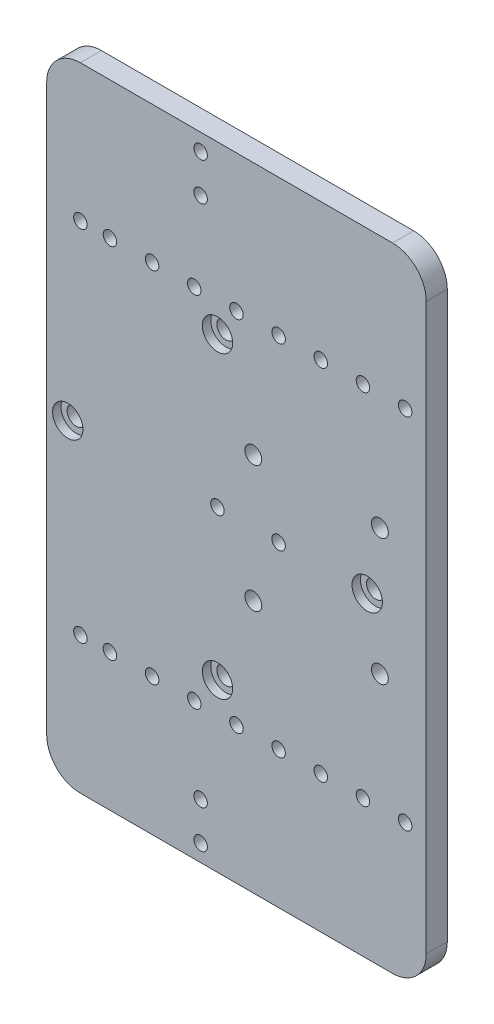
SolidWorks part; units mm, degrees
ref_plane "前视基准面" through (0, 0, 0) normal (0, 0, 1) x (1, 0, 0)
ref_plane "上视基准面" through (0, 0, 0) normal (0, 1, 0) x (1, 0, 0)
ref_plane "右视基准面" through (0, 0, 0) normal (1, 0, 0) x (0, 0, -1)
sketch "草图1" plane through (0, 0, 0) normal (0, 0, 1) x (1, 0, 0)
  line L1 (0, 0) -> (90, 0)
  line L2 (0, 0) -> (0, -150)
  line L3 (0, -150) -> (90, -150)
  line L4 (90, 0) -> (90, -150)
  circle A4 centre (79, -60) radius 2
  circle A5 centre (79, -90) radius 2
  circle A12 centre (49, -60) radius 2
  circle A13 centre (49, -90) radius 2
  circle A14 centre (40.5, -39.5) radius 2.15
  circle A15 centre (40.5, -110.5) radius 2.15
  circle A16 centre (76, -75) radius 2.15
  circle A17 centre (5, -75) radius 2.15
  circle A18 centre (85, -117.5) radius 1.6
  circle A19 centre (75, -117.5) radius 1.6
  circle A20 centre (65, -117.5) radius 1.6
  circle A21 centre (55, -117.5) radius 1.6
  circle A22 centre (45, -117.5) radius 1.6
  circle A23 centre (85, -32.5) radius 1.6
  circle A24 centre (75, -32.5) radius 1.6
  circle A25 centre (65, -32.5) radius 1.6
  circle A26 centre (55, -32.5) radius 1.6
  circle A27 centre (45, -32.5) radius 1.6
  circle A28 centre (35, -117.5) radius 1.6
  circle A29 centre (25, -117.5) radius 1.6
  circle A30 centre (15, -117.5) radius 1.6
  circle A31 centre (35, -32.5) radius 1.6
  circle A32 centre (25, -32.5) radius 1.6
  circle A33 centre (15, -32.5) radius 1.6
  circle A34 centre (8, -117.5) radius 1.6
  circle A35 centre (8, -32.5) radius 1.6
  circle A36 centre (36.5, -4) radius 1.6
  circle A37 centre (36.5, -13) radius 1.6
  circle A38 centre (36.5, -137) radius 1.6
  circle A39 centre (36.5, -146) radius 1.6
  circle A40 centre (55, -75) radius 1.6
  circle A41 centre (40.5, -75) radius 1.6
  dimension "D1" = 150
  dimension "D15" = 2
  dimension "D5" = 30
  dimension "D16" = 2
  dimension "D17" = 2
  dimension "D18" = 39.5
  dimension "D7" = 49
  dimension "D19" = 71
  dimension "D21" = 71
  dimension "D3" = 75
  dimension "D4" = 32.5
  dimension "D6" = 3.2
  dimension "D12" = 5
  dimension "D23" = 7
  dimension "D24" = 4
  dimension "D25" = 36.5
  dimension "D28" = 4
  dimension "D29" = 9
  dimension "D30" = 50
  dimension "D31" = 35.5
  dimension "D2" = 90
  dimension "D8" = 60
  dimension "D9" = 5
  dimension "D10" = 30
  dimension "D11" = 2
  dimension "D13" = 4
  dimension "D14" = 2
  dimension "D20" = 40.5
  dimension "D22" = 5
  dimension "D26" = 2
  dimension "D27" = 2
extrude "凸台-拉伸1" add sketch "草图1" along normal blind 5
fillet "圆角1" radius 8 4 edges at (0, -150, 2.5) (90, -150, 2.5) (90, 0, 2.5) (0, 0, 2.5)
sketch "草图2" plane through (0, 0, 5) normal (0, 0, 1) x (1, 0, 0)
  circle A0 centre (40.5, -39.5) radius 3.6
  circle A1 centre (76, -75) radius 3.6
  circle A2 centre (5, -75) radius 3.6
  circle A3 centre (40.5, -110.5) radius 3.6
  circle A5 centre (40.5, -39.5) radius 2.15 construction
  circle A6 centre (76, -75) radius 2.15 construction
  circle A7 centre (40.5, -110.5) radius 2.15 construction
  circle A8 centre (5, -75) radius 2.15 construction
extrude "切除-拉伸1" cut sketch "草图2" against normal blind 2
sketch "草图4" plane through (0, 0, 0) normal (0, 0, -1) x (-1, 0, 0)
  arc A0 (-42.1996, -35.0361) -> (-80.4639, -73.3004) centre (-40.5, -75) ccw
  arc A3 (-38.8004, -114.9639) -> (-42.1996, -114.9639) centre (-40.5, -110.5) ccw
  arc A4 (-80.4639, -76.6996) -> (-80.4639, -73.3004) centre (-76, -75) ccw
  arc A6 (-0.5361, -73.3004) -> (-0.5361, -76.6996) centre (-5, -75) ccw
  arc A7 (-42.1996, -35.0361) -> (-38.8004, -35.0361) centre (-40.5, -39.5) ccw
  arc A8 (-80.4639, -76.6996) -> (-42.1996, -114.9639) centre (-40.5, -75) ccw
  arc A9 (-38.8004, -114.9639) -> (-0.5361, -76.6996) centre (-40.5, -75) ccw
  arc A10 (-0.5361, -73.3004) -> (-38.8004, -35.0361) centre (-40.5, -75) ccw
  circle A11 centre (-40.5, -75) radius 30
extrude "凸台-拉伸2" add sketch "草图4" along normal blind 4
sketch "草图5" plane through (0, 0, -4) normal (0, 0, -1) x (-1, 0, 0)
  circle A0 centre (-79, -60) radius 4
  circle A1 centre (-79, -90) radius 4
extrude "切除-拉伸2" cut sketch "草图5" against normal blind 6
